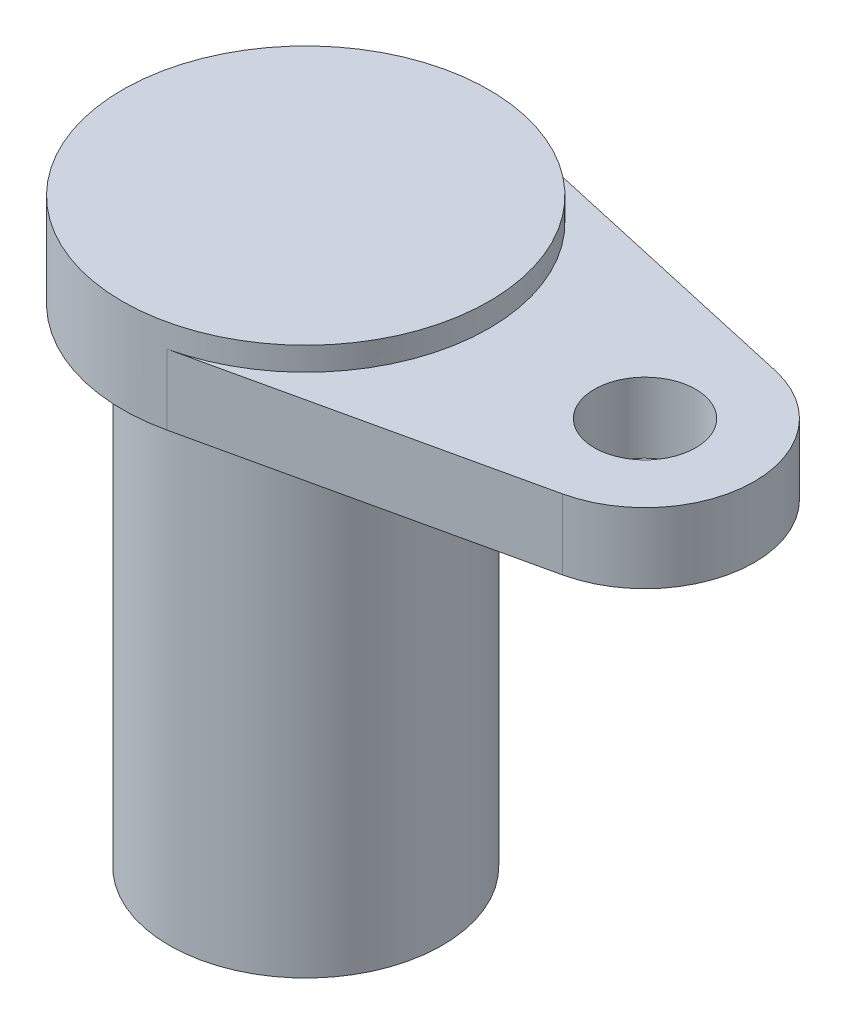
SolidWorks part; units mm, degrees
ref_plane "Front Plane" through (0, 0, 0) normal (0, 0, 1) x (1, 0, 0)
ref_plane "Top Plane" through (0, 0, 0) normal (0, 1, 0) x (1, 0, 0)
ref_plane "Right Plane" through (0, 0, 0) normal (1, 0, 0) x (0, 0, -1)
sketch "Sketch1" plane through (0, 0, 0) normal (0, 1, 0) x (1, 0, 0)
  circle A0 centre (0, 0) radius 8.89
  dimension "D1" = 17.78
extrude "Boss-Extrude1" add sketch "Sketch1" along normal blind 31.75
sketch "Sketch2" plane through (0, 31.75, 0) normal (0, 1, 0) x (1, 0, 0)
  line L0 (2.6071, 11.6498) -> (23.6512, 6.9403)
  line L1 (23.6512, -6.9403) -> (2.6071, -11.6498)
  circle A0 centre (0, 0) radius 11.938 construction
  circle A1 centre (22.098, 0) radius 7.112 construction
  arc A2 (2.6071, 11.6498) -> (2.6071, -11.6498) centre (0, 0) ccw
  arc A3 (23.6512, 6.9403) -> (23.6512, -6.9403) centre (22.098, 0) cw
  circle A4 centre (22.098, 0) radius 3.302
  point P5 (29.21, 0)
  point P6 (-11.938, 0)
  dimension "D1" = 23.876
  dimension "D4" = 6.604
  dimension "D2" = 22.098
  dimension "D3" = 41.148
extrude "Boss-Extrude2" add sketch "Sketch2" along normal blind 4.572
sketch "Sketch3" plane through (0, 36.322, 0) normal (0, 1, 0) x (1, 0, 0)
  circle A0 centre (0, 0) radius 11.938
  arc A1 (2.6071, 11.6498) -> (2.6071, -11.6498) centre (0, 0) ccw construction
extrude "Boss-Extrude3" add sketch "Sketch3" along normal blind 1.524
